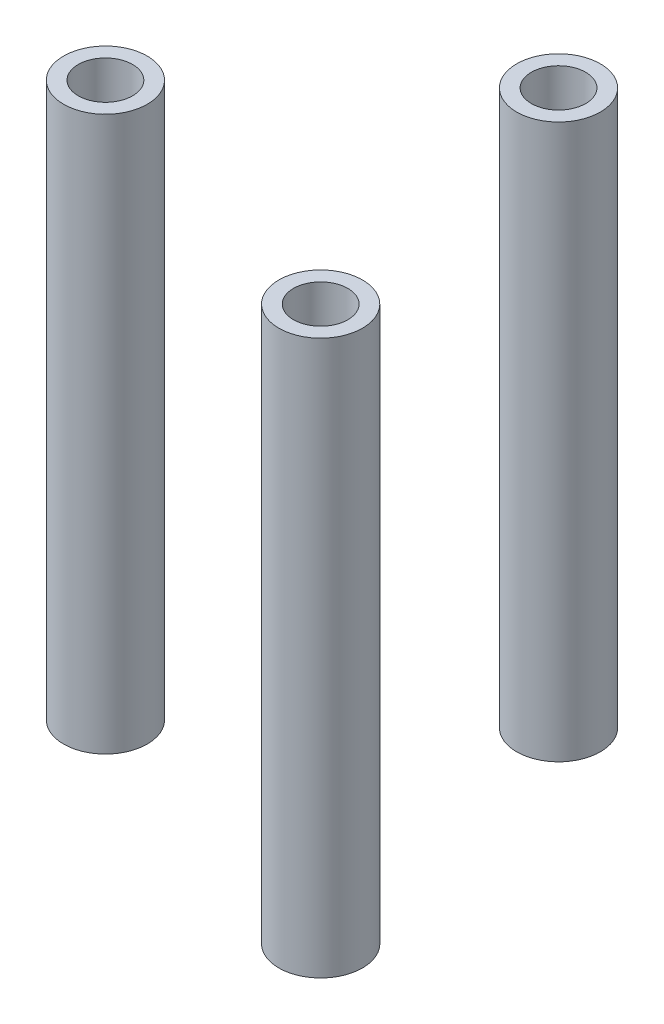
SolidWorks part; units mm, degrees
ref_plane "Front Plane" through (0, 0, 0) normal (0, 0, 1) x (1, 0, 0)
ref_plane "Top Plane" through (0, 0, 0) normal (0, 1, 0) x (1, 0, 0)
ref_plane "Right Plane" through (0, 0, 0) normal (1, 0, 0) x (0, 0, -1)
sketch "Sketch1" plane through (0, 0, 0) normal (0, 1, 0) x (1, 0, 0)
  line L1 (-29.9303, 30) -> (30.0697, 30)
  line L2 (-29.9303, 30) -> (-29.9303, -30)
  line L3 (-29.9303, -30) -> (30.0697, -30)
  line L4 (30.0697, 30) -> (30.0697, -30)
  circle A6 centre (0, 0) radius 17.45
  circle A7 centre (11.9677, -12.6995) radius 2.6
  circle A8 centre (-16.8744, -4.4451) radius 2.6
  circle A9 centre (5.4375, 16.5812) radius 2.6
  circle A10 centre (-16.8744, -4.4451) radius 4
  circle A11 centre (11.9677, -12.6995) radius 4
  circle A12 centre (5.4375, 16.5812) radius 4
  dimension "D3" = 5.2
  dimension "D4" = 5.2
  dimension "D5" = 5.2
  dimension "D6" = 34.9
  dimension "D10" = 8
  dimension "D1" = 60
  dimension "D2" = 60
  dimension "D7" = 30
  dimension "D8" = 30
  dimension "D9" = 30.6582
extrude "Boss-Extrude1" add sketch "Sketch1" along normal blind 53 contours A6 A10 A8 | A6 A10 A8 | A6 A11 A7 | A6 A11 A7 | A6 A12 A9 | A6 A12 A9
